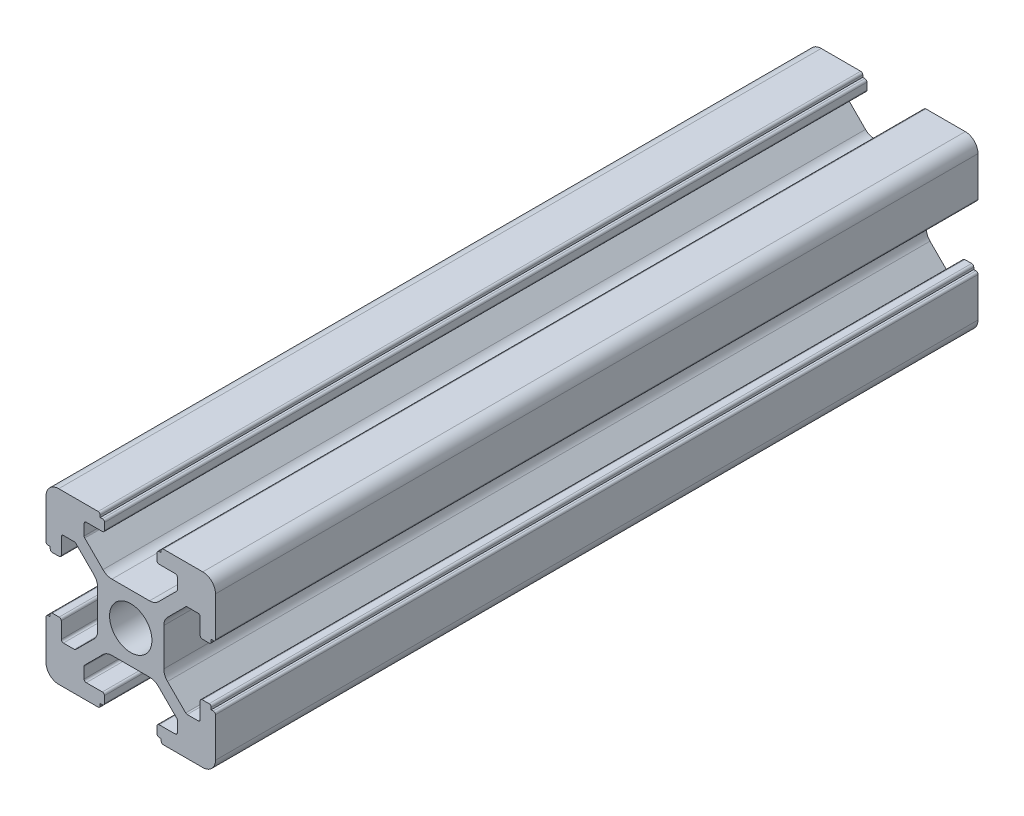
SolidWorks part; units mm, degrees
ref_plane "前视基准面" through (0, 0, 0) normal (0, 0, 1) x (1, 0, 0)
ref_plane "上视基准面" through (0, 0, 0) normal (0, 1, 0) x (1, 0, 0)
ref_plane "右视基准面" through (0, 0, 0) normal (1, 0, 0) x (0, 0, -1)
sketch "草图1" plane through (0, 0, 0) normal (0, 0, 1) x (1, 0, 0)
  line L0 (0, 0) -> (0, 5.5) construction
  line L1 (-8.5023, -10.0023) -> (-3.85, -10.0023)
  line L2 (-10.0023, -8.5023) -> (-10.0023, -3.85)
  line L3 (-8.5023, 10.0023) -> (-3.85, 10.0023)
  line L4 (10.0023, -8.5023) -> (10.0023, -3.85)
  line L5 (-10.0023, -10.0023) -> (10.0023, 10.0023) construction
  line L6 (-10.0023, 10.0023) -> (10.0023, -10.0023) construction
  line L7 (-2.218, -3.9) -> (2.218, -3.9)
  line L8 (-3.9, -2.218) -> (-3.9, 2.218)
  line L9 (-2.218, 3.9) -> (2.218, 3.9)
  line L10 (3.9, -2.218) -> (3.9, 2.218)
  line L11 (-3.9, -3.9) -> (3.9, 3.9) construction
  line L12 (-3.9, 3.9) -> (3.9, -3.9) construction
  line L13 (-5.25, -8.2) -> (-3.35, -8.2)
  line L14 (-8.2, -5.25) -> (-8.2, -3.35)
  line L15 (-5.25, 8.2) -> (-3.35, 8.2)
  line L16 (8.2, -5.25) -> (8.2, -3.35)
  line L17 (-8.2, -8.2) -> (8.2, 8.2) construction
  line L18 (-8.2, 8.2) -> (8.2, -8.2) construction
  line L19 (-7.95, 5.5) -> (-6.6642, 5.5)
  line L20 (0, 0) -> (5.5, 0) construction
  line L23 (-5.5, 7.95) -> (-5.5, 6.6642)
  line L26 (0, 0) -> (-0.5303, 0.5303)
  line L27 (3.2787, 4.3393) -> (5.4268, 6.4874)
  line L28 (0, 0) -> (0.5303, -0.5303)
  line L29 (5.5, 6.6642) -> (5.5, 7.95)
  line L30 (4.3393, 3.2787) -> (6.4874, 5.4268)
  line L31 (6.6642, 5.5) -> (7.95, 5.5)
  line L32 (4.3393, -3.2787) -> (6.4874, -5.4268)
  line L33 (3.2787, -4.3393) -> (5.4268, -6.4874)
  line L34 (-3.2787, -4.3393) -> (-5.4268, -6.4874)
  line L35 (-4.3393, -3.2787) -> (-6.4874, -5.4268)
  line L36 (-4.3393, 3.2787) -> (-6.4874, 5.4268)
  line L37 (-3.2787, 4.3393) -> (-5.4268, 6.4874)
  line L38 (3.1, -8.45) -> (3.1, -9.2523)
  line L39 (8.45, 3.1) -> (9.2523, 3.1)
  line L40 (-5.5, -6.6642) -> (-5.5, -7.95)
  line L41 (-6.6642, -5.5) -> (-7.95, -5.5)
  line L42 (5.5, -6.6642) -> (5.5, -7.95)
  line L43 (6.6642, -5.5) -> (7.95, -5.5)
  line L44 (9.2523, -3.1) -> (8.45, -3.1)
  line L46 (10.0023, 3.85) -> (10.0023, 8.5023)
  line L47 (8.2, 3.35) -> (8.2, 5.25)
  line L48 (-3.1, -9.2523) -> (-3.1, -8.45)
  line L49 (-8.45, -3.1) -> (-9.2523, -3.1)
  line L50 (-9.2523, 3.1) -> (-8.45, 3.1)
  line L51 (-3.1, 8.45) -> (-3.1, 9.2523)
  line L52 (3.1, 9.2523) -> (3.1, 8.45)
  line L53 (3.85, 10.0023) -> (8.5023, 10.0023)
  line L54 (3.35, 8.2) -> (5.25, 8.2)
  line L55 (-10.0023, 3.85) -> (-10.0023, 8.5023)
  line L56 (-8.2, 3.35) -> (-8.2, 5.25)
  line L57 (3.35, -8.2) -> (5.25, -8.2)
  line L58 (3.85, -10.0023) -> (8.5023, -10.0023)
  line L59 (9.7523, -3.6) -> (9.5023, -3.6)
  line L61 (9.7523, 3.6) -> (9.5023, 3.6)
  line L62 (9.5023, -3.6) -> (9.5023, -3.35)
  line L63 (3.6, -9.7523) -> (3.6, -9.5023)
  line L64 (3.35, -9.5023) -> (3.6, -9.5023)
  line L65 (9.5023, 3.35) -> (9.5023, 3.6)
  line L66 (-3.6, -9.5023) -> (-3.35, -9.5023)
  line L67 (-3.6, -9.7523) -> (-3.6, -9.5023)
  line L68 (-9.7523, -3.6) -> (-9.5023, -3.6)
  line L69 (-9.5023, -3.35) -> (-9.5023, -3.6)
  line L70 (-9.5023, 3.6) -> (-9.5023, 3.35)
  line L71 (-9.7523, 3.6) -> (-9.5023, 3.6)
  line L72 (-3.6, 9.7523) -> (-3.6, 9.5023)
  line L73 (-3.35, 9.5023) -> (-3.6, 9.5023)
  line L74 (3.6, 9.5023) -> (3.35, 9.5023)
  line L75 (3.6, 9.7523) -> (3.6, 9.5023)
  circle A0 centre (0, 0) radius 2.5
  arc A1 (10.0023, 8.5023) -> (8.5023, 10.0023) centre (8.5023, 8.5023) ccw
  arc A2 (8.5023, -10.0023) -> (10.0023, -8.5023) centre (8.5023, -8.5023) ccw
  arc A3 (-10.0023, -8.5023) -> (-8.5023, -10.0023) centre (-8.5023, -8.5023) ccw
  arc A4 (-10.0023, 8.5023) -> (-8.5023, 10.0023) centre (-8.5023, 8.5023) cw
  arc A5 (-9.5023, -3.35) -> (-9.2523, -3.1) centre (-9.2523, -3.35) cw
  arc A6 (-9.7523, -3.6) -> (-10.0023, -3.85) centre (-9.7523, -3.85) ccw
  arc A7 (-8.45, -3.1) -> (-8.2, -3.35) centre (-8.45, -3.35) cw
  arc A8 (-7.95, -5.5) -> (-8.2, -5.25) centre (-7.95, -5.25) cw
  arc A9 (-6.4874, -5.4268) -> (-6.6642, -5.5) centre (-6.6642, -5.25) cw
  arc A10 (-5.4268, -6.4874) -> (-5.5, -6.6642) centre (-5.25, -6.6642) ccw
  arc A11 (-5.5, -7.95) -> (-5.25, -8.2) centre (-5.25, -7.95) ccw
  arc A12 (-3.6, -9.7523) -> (-3.85, -10.0023) centre (-3.85, -9.7523) cw
  arc A13 (-3.35, -9.5023) -> (-3.1, -9.2523) centre (-3.35, -9.2523) ccw
  arc A14 (-3.1, -8.45) -> (-3.35, -8.2) centre (-3.35, -8.45) ccw
  arc A15 (3.1, -8.45) -> (3.35, -8.2) centre (3.35, -8.45) cw
  arc A16 (5.5, -7.95) -> (5.25, -8.2) centre (5.25, -7.95) cw
  arc A17 (5.4268, -6.4874) -> (5.5, -6.6642) centre (5.25, -6.6642) cw
  arc A18 (6.4874, -5.4268) -> (6.6642, -5.5) centre (6.6642, -5.25) ccw
  arc A19 (7.95, -5.5) -> (8.2, -5.25) centre (7.95, -5.25) ccw
  arc A20 (8.45, -3.1) -> (8.2, -3.35) centre (8.45, -3.35) ccw
  arc A21 (9.5023, -3.35) -> (9.2523, -3.1) centre (9.2523, -3.35) ccw
  arc A22 (9.7523, -3.6) -> (10.0023, -3.85) centre (9.7523, -3.85) cw
  arc A23 (3.35, -9.5023) -> (3.1, -9.2523) centre (3.35, -9.2523) cw
  arc A24 (3.6, -9.7523) -> (3.85, -10.0023) centre (3.85, -9.7523) ccw
  arc A25 (7.95, 5.5) -> (8.2, 5.25) centre (7.95, 5.25) cw
  arc A26 (8.2, 3.35) -> (8.45, 3.1) centre (8.45, 3.35) ccw
  arc A27 (9.5023, 3.35) -> (9.2523, 3.1) centre (9.2523, 3.35) cw
  arc A28 (9.7523, 3.6) -> (10.0023, 3.85) centre (9.7523, 3.85) ccw
  arc A29 (6.6642, 5.5) -> (6.4874, 5.4268) centre (6.6642, 5.25) ccw
  arc A30 (5.4268, 6.4874) -> (5.5, 6.6642) centre (5.25, 6.6642) ccw
  arc A31 (5.5, 7.95) -> (5.25, 8.2) centre (5.25, 7.95) ccw
  arc A32 (3.1, 8.45) -> (3.35, 8.2) centre (3.35, 8.45) ccw
  arc A33 (3.6, 9.7523) -> (3.85, 10.0023) centre (3.85, 9.7523) cw
  arc A34 (3.35, 9.5023) -> (3.1, 9.2523) centre (3.35, 9.2523) ccw
  arc A35 (-9.7523, 3.6) -> (-10.0023, 3.85) centre (-9.7523, 3.85) cw
  arc A36 (-9.5023, 3.35) -> (-9.2523, 3.1) centre (-9.2523, 3.35) ccw
  arc A37 (-8.45, 3.1) -> (-8.2, 3.35) centre (-8.45, 3.35) ccw
  arc A38 (-8.2, 5.25) -> (-7.95, 5.5) centre (-7.95, 5.25) cw
  arc A39 (-6.4874, 5.4268) -> (-6.6642, 5.5) centre (-6.6642, 5.25) ccw
  arc A40 (-5.4268, 6.4874) -> (-5.5, 6.6642) centre (-5.25, 6.6642) cw
  arc A41 (-5.5, 7.95) -> (-5.25, 8.2) centre (-5.25, 7.95) cw
  arc A42 (-3.1, 8.45) -> (-3.35, 8.2) centre (-3.35, 8.45) cw
  arc A43 (-3.1, 9.2523) -> (-3.35, 9.5023) centre (-3.35, 9.2523) ccw
  arc A44 (-3.6, 9.7523) -> (-3.85, 10.0023) centre (-3.85, 9.7523) ccw
  arc A45 (-4.3393, 3.2787) -> (-3.9, 2.218) centre (-5.4, 2.218) cw
  arc A46 (-3.2787, 4.3393) -> (-2.218, 3.9) centre (-2.218, 5.4) ccw
  arc A47 (3.2787, 4.3393) -> (2.218, 3.9) centre (2.218, 5.4) cw
  arc A48 (4.3393, 3.2787) -> (3.9, 2.218) centre (5.4, 2.218) ccw
  arc A49 (4.3393, -3.2787) -> (3.9, -2.218) centre (5.4, -2.218) cw
  arc A50 (3.2787, -4.3393) -> (2.218, -3.9) centre (2.218, -5.4) ccw
  arc A51 (-4.3393, -3.2787) -> (-3.9, -2.218) centre (-5.4, -2.218) ccw
  arc A52 (-2.218, -3.9) -> (-3.2787, -4.3393) centre (-2.218, -5.4) ccw
  point P0 (0, 0)
  point P7 (10.0023, 0)
  point P62 (0, 0)
  point P76 (0, 0)
  point P92 (-8.2, -5.5)
  point P99 (0, 0)
  point P106 (-5.5, -8.2)
  point P117 (5.5, -8.2)
  point P124 (8.2, -5.5)
  point P137 (8.2, 5.5)
  point P140 (8.2, 3.1)
  point P147 (6.5607, 5.5)
  point P152 (5.5, 8.2)
  point P167 (-8.2, 5.5)
  point P174 (-5.5, 8.2)
  dimension "D1" = 1.5
  dimension "D5" = 0.25
  dimension "D6" = 1.5
  dimension "D2" = 4
  dimension "D3" = 4
  dimension "D4" = 4
extrude "凸台-拉伸1" add sketch "草图1" along normal mid plane 90 contours A52 L7 A50 L33 A17 L42 A16 L57 A15 L38 A23 L64 L63 A24 L58 A2 L4 A22 L59 L62 A21 L44 A20 L16 A19 L43 A18 L32 A49 L10 A48 L30 A29 L31 A25 L47 A26 L39 A27 L65 L61 A28 L46 A1 L53 A33 L75 L74 A34 L52 A32
